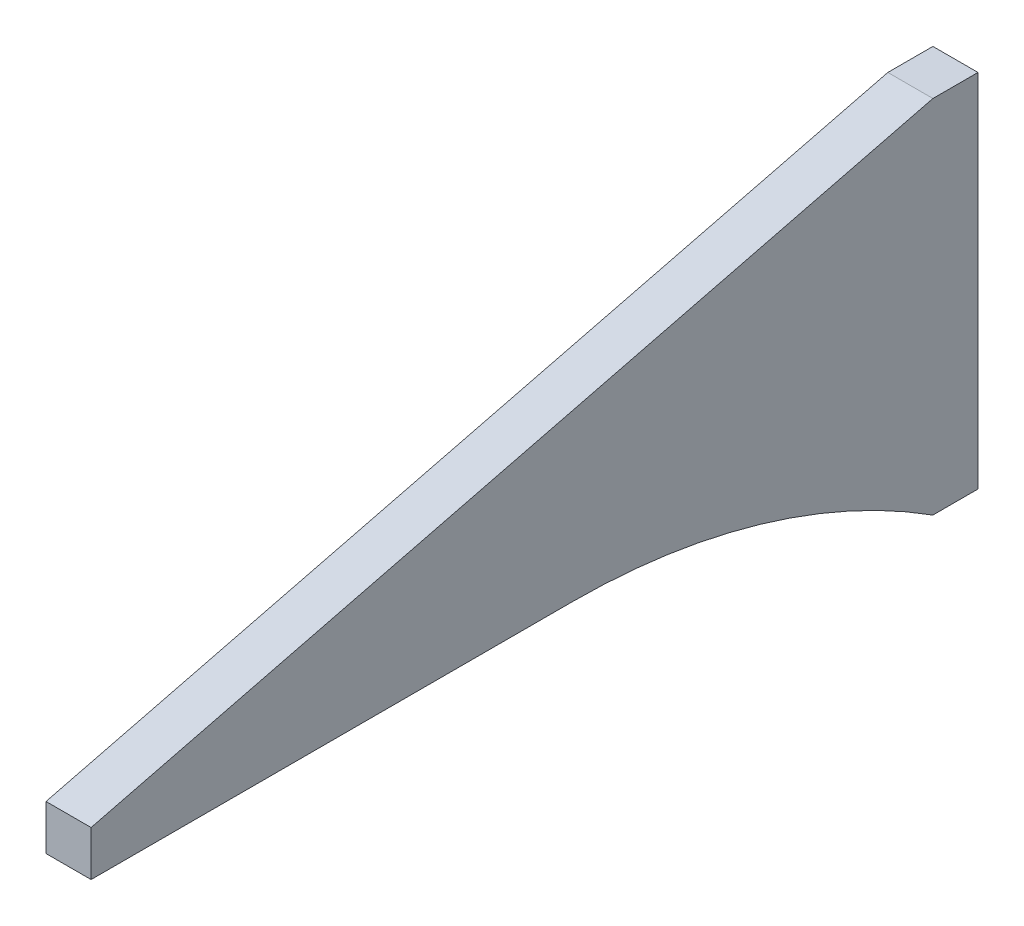
SolidWorks part; units mm, degrees
material "Pine"
ref_plane "Front Plane" through (0, 0, 0) normal (0, 0, 1) x (1, 0, 0)
ref_plane "Top Plane" through (0, 0, 0) normal (0, 1, 0) x (1, 0, 0)
ref_plane "Right Plane" through (0, 0, 0) normal (1, 0, 0) x (0, 0, -1)
sketch "Sketch1" plane through (0, 0, 0) normal (1, 0, 0) x (0, 0, -1)
  line L0 (0, 0) -> (203.2, 0)
  line L1 (0, 0) -> (0, 19.05)
  line L2 (374.65, 107.95) -> (355.6, 107.95)
  line L3 (374.65, 107.95) -> (374.65, -44.45)
  line L4 (374.65, -44.45) -> (355.6, -44.45)
  line L5 (355.6, 107.95) -> (0, 19.05)
  arc A0 (203.2, 0) -> (355.6, -44.45) centre (203.2, -283.4821) cw
  dimension "D1" = 203.2
  dimension "D2" = 152.4
  dimension "D3" = 88.9
  dimension "D4" = 374.65
  dimension "D5" = 19.05
  dimension "D6" = 19.05
  dimension "D7" = 19.05
extrude "Boss-Extrude1" add sketch "Sketch1" along normal blind 19.05
